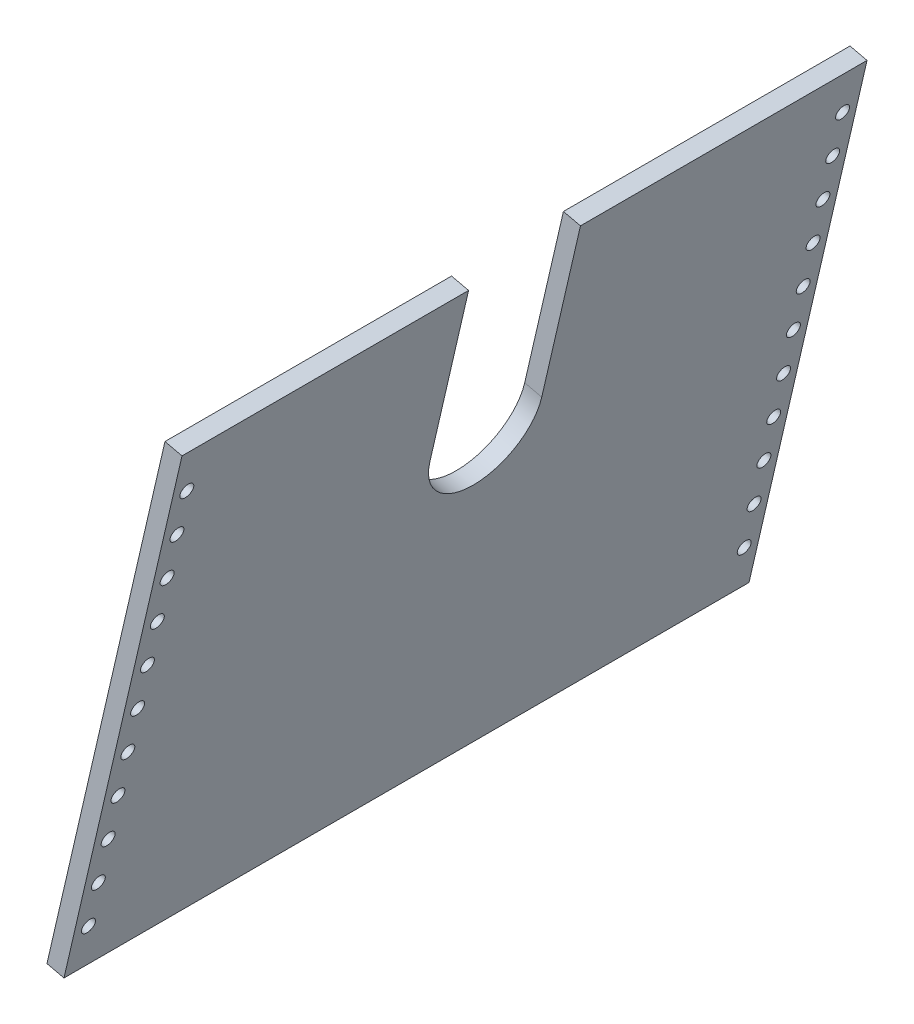
SolidWorks part; units mm, degrees
material "Gillfab4009"
ref_plane "Front Plane" through (0, 0, 0) normal (0, 0, 1) x (1, 0, 0)
ref_plane "Top Plane" through (0, 0, 0) normal (0, 1, 0) x (1, 0, 0)
ref_plane "Right Plane" through (0, 0, 0) normal (1, 0, 0) x (0, 0, -1)
sketch "Sketch1" plane through (0, 0, 0) normal (0, 0, 1) x (1, 0, 0)
  line L0 (130.4243, 1639.6605) -> (117.4836, 1583.6084) construction
  line L1 (174.2078, 1829.308) -> (105.6428, 1532.32)
  line L2 (105.6428, 1532.32) -> (95.7432, 1534.6055)
  line L4 (95.7432, 1534.6055) -> (164.3082, 1831.5935)
  line L5 (164.3082, 1831.5935) -> (174.2078, 1829.308)
  line L6 (10.16, 2052.32) -> (91.4769, 2052.32) construction
  dimension "D1" = 520
  dimension "D2" = 304.8
extrude "Boss-Extrude1" add sketch "Sketch1" along normal blind 398
sketch "Sketch2" plane through (-235.5655, 54.3846, 0) normal (0.9744, -0.225, 0) x (0, 0, -1)
  line L0 (-199, 1821.6112) -> (-199, 1721.6112) construction
  line L1 (-398, 1821.6112) -> (0, 1821.6112) construction
  line L2 (-199, 1721.6112) -> (-199, 1821.6112) construction
  line L3 (-231.5, 1721.6112) -> (-231.5, 1821.6112)
  line L4 (-166.5, 1721.6112) -> (-166.5, 1821.6112)
  line L5 (-166.5, 1821.6112) -> (-231.5, 1821.6112)
  arc A0 (-231.5, 1721.6112) -> (-166.5, 1721.6112) centre (-199, 1721.6112) ccw
  point P4 (-200, 1766.3816)
  dimension "D1" = 65
  dimension "D2" = 100
extrude "Cut-Extrude1" cut sketch "Sketch2" against normal through all both and the other way through all
sketch "Sketch3" plane through (-235.5655, 54.3846, 0) normal (0.9744, -0.225, 0) x (0, 0, -1)
  line L0 (-199, 1516.8112) -> (-199, 1827.1106) construction
  line L1 (-398, 1516.8112) -> (0, 1516.8112) construction
  line L2 (-398, 1669.2112) -> (0, 1669.2112) construction
  line L3 (-398, 1516.8112) -> (-398, 1821.6112) construction
  line L4 (0, 1516.8112) -> (0, 1821.6112) construction
  line L5 (-389.5, 1669.2112) -> (-8.5, 1669.2112) construction
  circle A0 centre (-389.5, 1669.2112) radius 3.9688
  circle A1 centre (-389.5, 1694.6112) radius 3.9688
  circle A2 centre (-389.5, 1720.0112) radius 3.9688
  circle A3 centre (-389.5, 1745.4112) radius 3.9688
  circle A4 centre (-389.5, 1770.8112) radius 3.9688
  circle A5 centre (-389.5, 1796.2112) radius 3.9688
  circle A6 centre (-389.5, 1542.2112) radius 3.9688
  circle A7 centre (-389.5, 1567.6112) radius 3.9688
  circle A8 centre (-389.5, 1593.0112) radius 3.9688
  circle A9 centre (-389.5, 1618.4112) radius 3.9688
  circle A10 centre (-389.5, 1643.8112) radius 3.9688
  circle A11 centre (-8.5, 1643.8112) radius 3.9688
  circle A12 centre (-8.5, 1618.4112) radius 3.9688
  circle A13 centre (-8.5, 1593.0112) radius 3.9688
  circle A14 centre (-8.5, 1567.6112) radius 3.9688
  circle A15 centre (-8.5, 1542.2112) radius 3.9688
  circle A16 centre (-8.5, 1796.2112) radius 3.9688
  circle A17 centre (-8.5, 1770.8112) radius 3.9688
  circle A18 centre (-8.5, 1745.4112) radius 3.9688
  circle A19 centre (-8.5, 1720.0112) radius 3.9688
  circle A20 centre (-8.5, 1694.6112) radius 3.9688
  circle A21 centre (-8.5, 1669.2112) radius 3.9687
  point P13 (-199, 1669.2112)
  dimension "D2" = 7.9375
  dimension "D1" = 381
  dimension "D3" = 6
extrude "Cut-Extrude3" cut sketch "Sketch3" against normal through all
